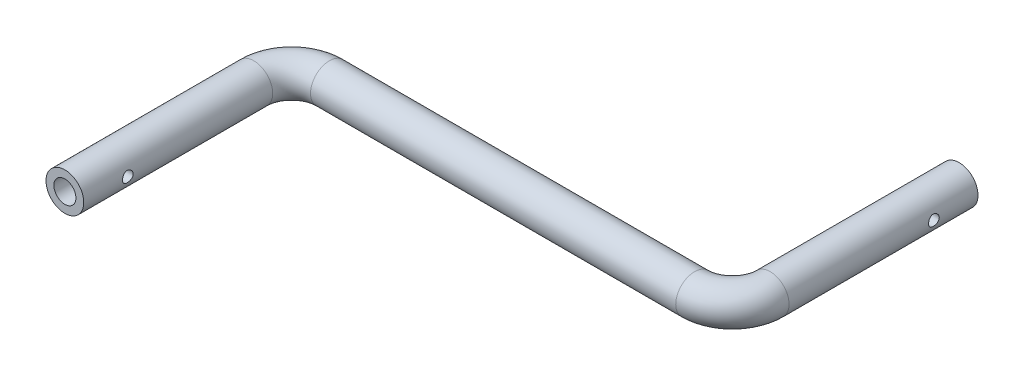
SolidWorks part; units mm, degrees
material "1060 Alloy"
ref_plane "Plano frontal" through (0, 0, 0) normal (0, 0, 1) x (1, 0, 0)
ref_plane "Plano superior" through (0, 0, 0) normal (0, 1, 0) x (1, 0, 0)
ref_plane "Plano direito" through (0, 0, 0) normal (1, 0, 0) x (0, 0, -1)
sketch "Sketch1" plane through (0, 0, 0) normal (0, 1, 0) x (1, 0, 0)
  line L0 (-145, 0) -> (145, 0)
  line L1 (175, 30) -> (175, 180)
  line L2 (-175, -180) -> (-175, -30)
  arc A0 (145, 0) -> (175, 30) centre (145, 30) ccw
  arc A1 (-175, -30) -> (-145, 0) centre (-145, -30) cw
  point P4 (0, 0)
  dimension "D1" = 30
  dimension "D2" = 350
  dimension "D3" = 150
  dimension "D4" = 150
sketch "Sketch2" plane through (0, 0, 0) normal (1, 0, 0) x (0, 0, -1)
  circle A0 centre (0, 0) radius 15
  circle A1 centre (0, 0) radius 8.75
  dimension "D1" = 30
  dimension "D2" = 17.5
sweep "Sweep1" add profiles "Sketch2" path "Sketch1"
sketch "Sketch9" plane through (0, 0, 0) normal (1, 0, 0) x (0, 0, -1)
  line L0 (0, 16.5) -> (0, -16.5) construction
  circle A0 centre (-145, 0) radius 5
  circle A1 centre (145, 0) radius 5
  point P7 (0, 0)
  dimension "D1" = 10
  dimension "D2" = 145
hole_wizard "M10 Tapped Hole1" positions "3DSketch14" profile "Sketch18" tap size "M10" standard "ISO" end condition through all
sketch3d "3DSketch14"
  point P0 (-190, 0, 145)
sketch "Sketch18" plane through (-190, 0, 145) normal (0, 1, 0) x (0, 0, 1)
  line L0 (0, 0) -> (0, 380)
  line L1 (0, 380) -> (4.25, 380)
  line L2 (4.25, 380) -> (4.25, 0)
  line L5 (4.25, 0) -> (0, 0)
  line L11 (0, -6.35) -> (0, 107.95) construction
  dimension "Thread Major Dia." = 8.5
  dimension "Thru Tap Drill Depth" = 380
hole_wizard "M10 Tapped Hole2" positions "3DSketch15" profile "Sketch19" tap size "M10" standard "ISO" end condition through all
sketch3d "3DSketch15"
  point P0 (190, 0, -145)
sketch "Sketch19" plane through (190, 0, -145) normal (0, 1, 0) x (0, 0, -1)
  line L0 (0, 0) -> (0, 380)
  line L1 (0, 380) -> (4.25, 380)
  line L2 (4.25, 380) -> (4.25, 0)
  line L5 (4.25, 0) -> (0, 0)
  line L11 (0, -6.35) -> (0, 107.95) construction
  dimension "Thread Major Dia." = 8.5
  dimension "Thru Tap Drill Depth" = 380
